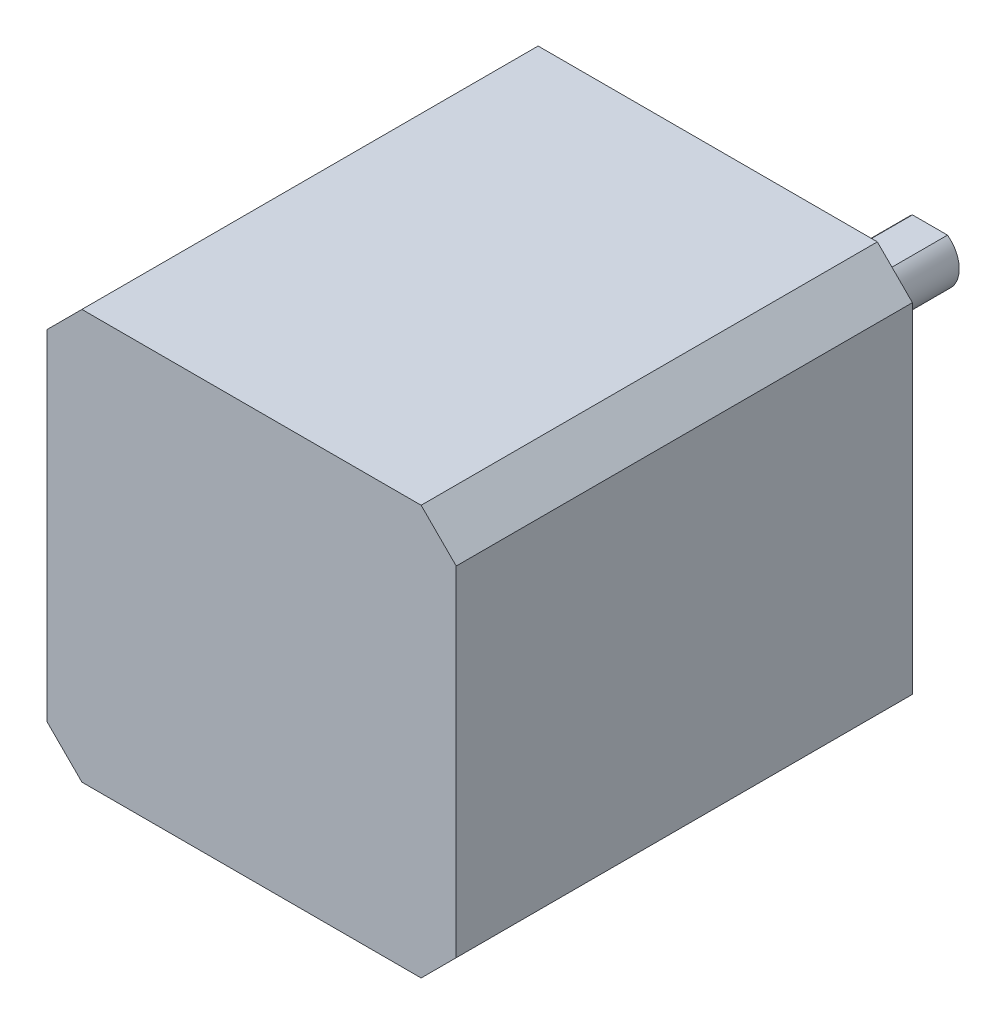
SolidWorks part; units mm, degrees
ref_plane "前视基准面" through (0, 0, 0) normal (0, 0, 1) x (1, 0, 0)
ref_plane "上视基准面" through (0, 0, 0) normal (0, 1, 0) x (1, 0, 0)
ref_plane "右视基准面" through (0, 0, 0) normal (1, 0, 0) x (0, 0, -1)
other "Configuration Table"
sketch "草图1" plane through (0, 0, 0) normal (0, 0, 1) x (1, 0, 0)
  line L1 (-17.5, -17.5) -> (17.5, -17.5)
  line L2 (-17.5, -17.5) -> (-17.5, 17.5)
  line L3 (-17.5, 17.5) -> (17.5, 17.5)
  line L4 (17.5, -17.5) -> (17.5, 17.5)
  line L5 (-17.5, -17.5) -> (17.5, 17.5) construction
  line L6 (-17.5, 17.5) -> (17.5, -17.5) construction
  point P0 (0, 0)
  dimension "D1" = 35
  dimension "D2" = 35
extrude "凸台-拉伸1" add sketch "草图1" along normal blind 39
sketch "草图2" plane through (0, 0, 0) normal (0, 0, -1) x (-1, 0, 0)
  circle A0 centre (0, 0) radius 11
  dimension "D1" = 22
extrude "凸台-拉伸2" add sketch "草图2" along normal blind 2
sketch "草图3" plane through (0, 0, -2) normal (0, 0, -1) x (-1, 0, 0)
  line L0 (-1.5, 2) -> (1.5, 2)
  arc A0 (-1.5, 2) -> (1.5, 2) centre (0, 0) ccw
  point P5 (0, 2.5)
  point P7 (-1.5, 2)
  point P8 (1.5, 2)
  dimension "D1" = 5
  dimension "D2" = 0.5
extrude "凸台-拉伸3" add sketch "草图3" along normal blind 17
chamfer "倒角1" distance 3 angle 45 4 edges at (17.5, -17.5, 19.5) (-17.5, -17.5, 19.5) (-17.5, 17.5, 19.5) (17.5, 17.5, 19.5)
